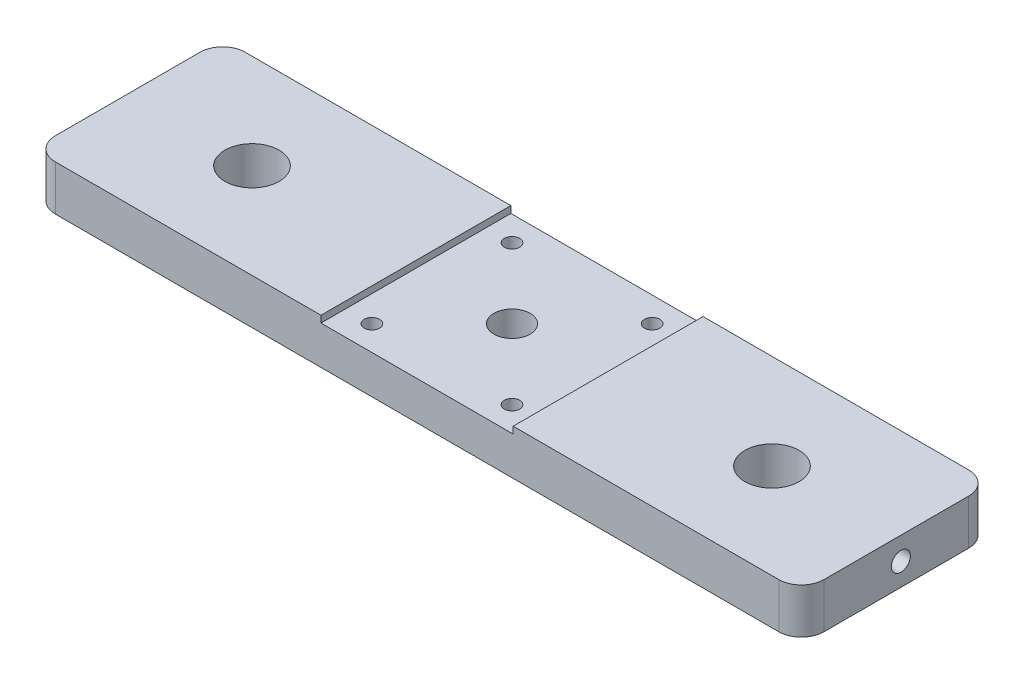
SolidWorks part; units mm, degrees
material "Liga 1060"
ref_plane "Frontal" through (0, 0, 0) normal (0, 0, 1) x (1, 0, 0)
ref_plane "Superior" through (0, 0, 0) normal (0, 1, 0) x (1, 0, 0)
ref_plane "Direito" through (0, 0, 0) normal (1, 0, 0) x (0, 0, -1)
sketch "Esboço1" plane through (0, 0, 0) normal (0, 1, 0) x (1, 0, 0)
  line L0 (-57.5, 0) -> (57.5, 0) construction
  line L1 (-85, 21) -> (85, 21)
  line L2 (-85, 21) -> (-85, -21)
  line L3 (-85, -21) -> (85, -21)
  line L4 (85, 21) -> (85, -21)
  line L5 (-85, 21) -> (85, -21) construction
  line L6 (-85, -21) -> (85, 21) construction
  circle A0 centre (-57.5, 0) radius 6
  circle A1 centre (57.5, 0) radius 6
  circle A2 centre (0, 0) radius 4
  point P0 (0, 0)
  dimension "D6" = 12
  dimension "D7" = 12
  dimension "D15" = 8
  dimension "D1" = 170
  dimension "D3" = 27.5
  dimension "D4" = 42
  dimension "D8" = 27.5
extrude "Ressalto-extrusão1" add sketch "Esboço1" along normal blind 10
hole_wizard "Furo roscado de M51" positions "Esboço3" profile "Esboço2" tap size "M5" standard "ISO"
sketch "Esboço3" plane through (85, 0, 0) normal (1, 0, 0) x (0, 0, -1)
  line L0 (-21, 10) -> (21, 10) construction
  line L1 (21, 10) -> (21, 0) construction
  point P0 (1, 5)
  dimension "D1" = 5
  dimension "D2" = 20
sketch "Esboço2" plane through (85, 5, -1) normal (0, 1, 0) x (0, 0, -1)
  line L0 (0, 0) -> (0, 15.2618)
  line L1 (0, 15.2618) -> (2.1, 14)
  line L2 (2.1, 14) -> (2.1, 0)
  line L5 (2.1, 0) -> (0, 0)
  line L10 (0, 15.2618) -> (-2.1, 14) construction
  line L11 (0, -6.35) -> (0, 107.95) construction
  dimension "Tap Drill Dia." = 4.2
  dimension "Tap Drill Depth" = 14
  dimension "Drill Angle" = 118
cosmetic thread "Rosca de furo1"
mirror "Espelhar1" about plane through (0, 0, 0) normal (1, 0, 0) of "Furo roscado de M51"
hole_wizard "Rebaixo para parafuso com cabeça panela de M31" positions "Esboço5" profile "Esboço4" counterbore size "M3" standard "ISO" end condition through all
sketch "Esboço5" plane through (0, 0, 0) normal (0, -1, 0) x (-1, 0, 0)
  line L0 (-50, 0) -> (50, 0) construction
  point P0 (-15.5, 15.5)
  point P2 (15.5, 15.5)
  point P8 (-15.5, -15.5)
  point P9 (15.5, -15.5)
  dimension "D1" = 31
  dimension "D2" = 15.5
  dimension "D3" = 15.5
sketch "Esboço4" plane through (15.5, 0, -15.5) normal (1, 0, 0) x (0, 0, -1)
  line L0 (0, 0) -> (0, 10)
  line L1 (0, 10) -> (1.7, 10)
  line L3 (1.7, 10) -> (1.7, 2.4)
  line L4 (1.7, 2.4) -> (3.5, 2.4)
  line L5 (3.5, 2.4) -> (3.5, 0)
  line L7 (3.5, 0) -> (0, 0)
  line L11 (0, -6.35) -> (0, 107.95) construction
  dimension "Thru Hole Dia." = 3.4
  dimension "Thru Hole Depth" = 10
  dimension "C'Bore Dia." = 7
  dimension "C'Bore Depth" = 2.4
sketch "Esboço7" plane through (0, 10, 0) normal (0, 1, 0) x (1, 0, 0)
  line L1 (-21.25, 23.1978) -> (21.25, 23.1978)
  line L2 (-21.25, 23.1978) -> (-21.25, -23.2)
  line L3 (-21.25, -23.2) -> (21.25, -23.2)
  line L4 (21.25, 23.1978) -> (21.25, -23.2)
  line L5 (0, -23.1978) -> (0, 23.1978) construction
  line L6 (85, 21) -> (-85, 21) construction
  line L7 (-85, -21) -> (85, -21) construction
  point P8 (0, 0)
  point P10 (0, 23.1978)
  dimension "D1" = 42.5
  dimension "D2" = 2.1978
  dimension "D3" = 2.2
extrude "Corte-extrusão2" cut sketch "Esboço7" against normal blind 1.5
fillet "Filete1" radius 5 4 edges at (-85, 5, 21) (-85, 5, -21) (85, 5, -21) (85, 5, 21)
